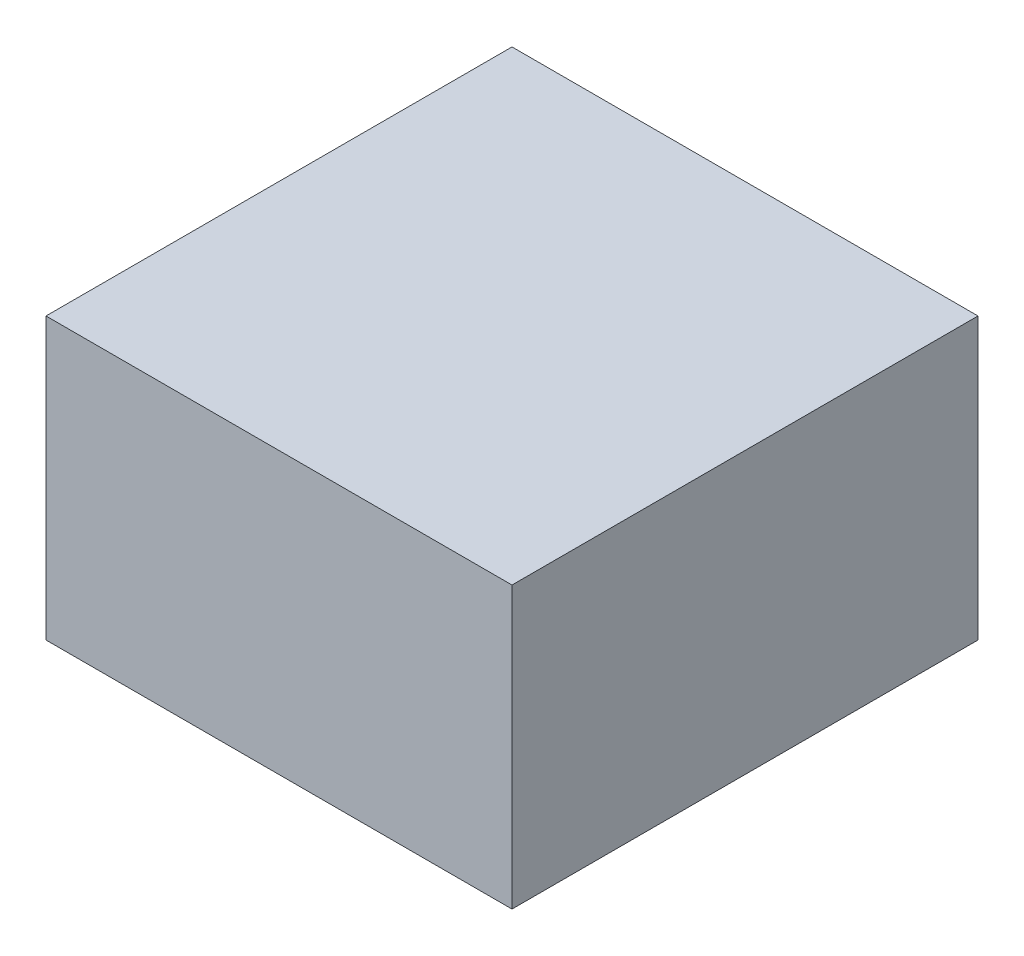
SolidWorks part; units mm, degrees
ref_plane "前基準面" through (0, 0, 0) normal (0, 0, 1) x (1, 0, 0)
ref_plane "上基準面" through (0, 0, 0) normal (0, 1, 0) x (1, 0, 0)
ref_plane "右基準面" through (0, 0, 0) normal (1, 0, 0) x (0, 0, -1)
sketch "草圖1" plane through (0, 0, 0) normal (0, 1, 0) x (1, 0, 0)
  line L1 (-22, 22) -> (22, 22)
  line L2 (-22, 22) -> (-22, -22)
  line L3 (-22, -22) -> (22, -22)
  line L4 (22, 22) -> (22, -22)
  line L5 (-22, 22) -> (22, -22) construction
  line L6 (-22, -22) -> (22, 22) construction
  point P0 (0, 0)
  dimension "D1" = 44
  dimension "D2" = 44
extrude "填料-伸長1" add sketch "草圖1" along normal blind 26.5
